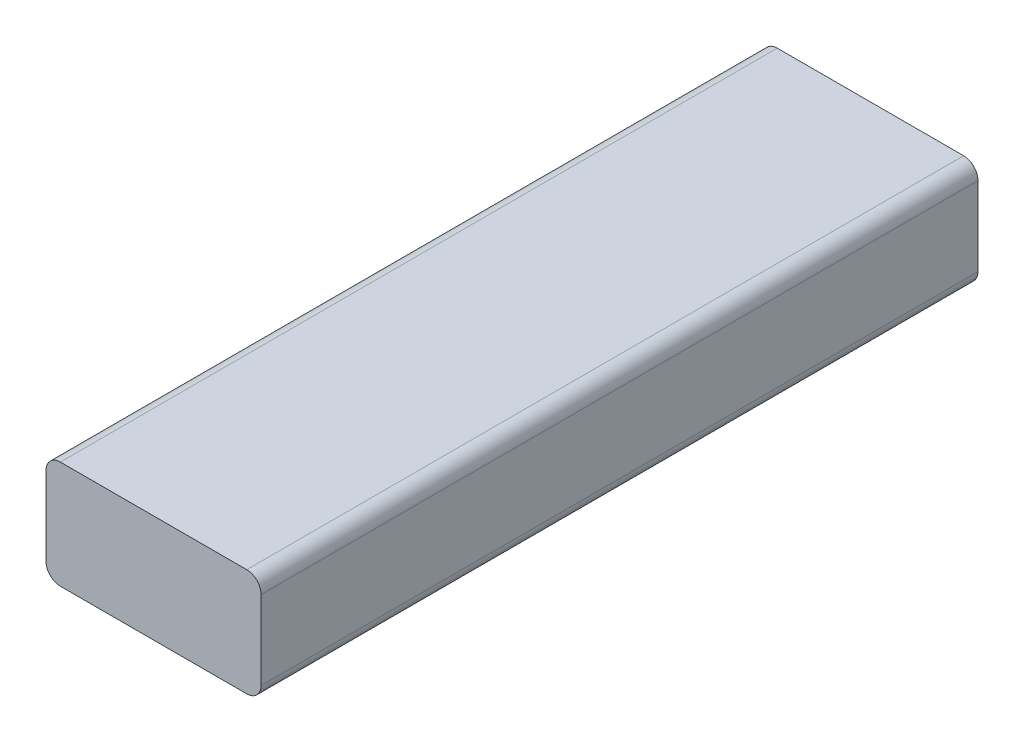
SolidWorks part; units mm, degrees
ref_plane "Front Plane" through (0, 0, 0) normal (0, 0, 1) x (1, 0, 0)
ref_plane "Top Plane" through (0, 0, 0) normal (0, 1, 0) x (1, 0, 0)
ref_plane "Right Plane" through (0, 0, 0) normal (1, 0, 0) x (0, 0, -1)
sketch "Sketch1" plane through (0, 0, 0) normal (0, 0, 1) x (1, 0, 0)
  line L1 (0, 0) -> (76.2, 0)
  line L2 (0, 0) -> (0, 38.1)
  line L3 (0, 38.1) -> (76.2, 38.1)
  line L4 (76.2, 0) -> (76.2, 38.1)
  dimension "D1" = 38.1
  dimension "D2" = 76.2
extrude "Boss-Extrude1" add sketch "Sketch1" along normal blind 254
fillet "Fillet1" radius 5.08 4 edges at (0, 0, 127) (0, 38.1, 127) (76.2, 0, 127) (76.2, 38.1, 127)
